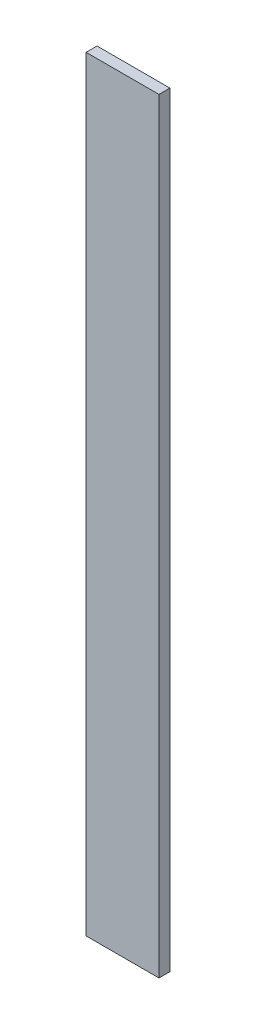
SolidWorks part; units mm, degrees
material "ASTM A36 Steel"
ref_plane "Front Plane" through (0, 0, 0) normal (0, 0, 1) x (1, 0, 0)
ref_plane "Top Plane" through (0, 0, 0) normal (0, 1, 0) x (1, 0, 0)
ref_plane "Right Plane" through (0, 0, 0) normal (1, 0, 0) x (0, 0, -1)
sketch "Sketch1" plane through (0, 0, 0) normal (0, 0, 1) x (1, 0, 0)
  line L1 (-20, -210) -> (20, -210)
  line L2 (-20, -210) -> (-20, 210)
  line L3 (-20, 210) -> (20, 210)
  line L4 (20, -210) -> (20, 210)
  line L5 (-20, -210) -> (20, 210) construction
  line L6 (-20, 210) -> (20, -210) construction
  point P0 (0, 0)
  dimension "D1" = 40
  dimension "D2" = 420
extrude "Boss-Extrude1" add sketch "Sketch1" along normal blind 6
